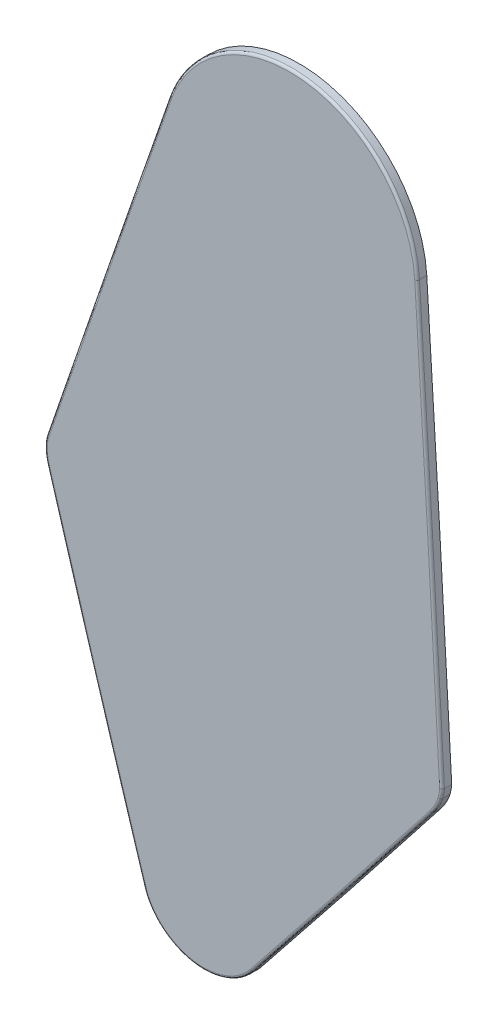
SolidWorks part; units mm, degrees
material "Glass"
ref_plane "Front Plane" through (0, 0, 0) normal (1, 0, 0) x (0, 1, 0)
ref_plane "Top Plane" through (0, 0, 0) normal (0, 0, 1) x (0, 1, 0)
ref_plane "Right Plane" through (0, 0, 0) normal (0, 1, 0) x (-1, 0, 0)
ref_plane "Plane1" through (0, 0, 4) normal (0, 0, 1) x (0, -1, 0)
sketch "Sketch1" plane through (0, 0, 4) normal (0, 0, 1) x (0, -1, 0)
  spline S0 degree 3 poles (-1420.5523, -1258.0609) (-9.2087, -51.8049) (117.8743, 15.8201) (141.0894, -9.406) (141.445, -9.8521) (141.934, -10.5605) (142.0901, -10.8041) (142.3838, -11.2982) (142.5217, -11.5491) (142.9098, -12.3131) (143.134, -12.8375) (143.5137, -13.9162) (143.6701, -14.4742) (143.9078, -15.5951) (143.99, -16.1591) (144.0816, -17.2938) (144.0912, -17.8646) (144.0507, -18.7259) (144.0279, -19.014) (143.9645, -19.5839) (143.8425, -20.4321) (143.6405, -21.2609) (143.386, -22.077) (143.2924, -22.347) (143.0873, -22.8824) (142.9753, -23.1489) (142.3761, -24.4546) (141.7722, -25.418) (140.6814, -26.7427) (140.2836, -27.1652) (139.4464, -27.9421) (139.0049, -28.3001) (138.075, -28.9535) (137.5866, -29.2488) (109.7491, -43.3088) (30.8578, 50.8341) (-150.7129, 1947.6032) knots -3.635484 -3.635484 -3.635484 -3.635484 0.0625 0.0625 0.125 0.125 0.15625 0.15625 0.1875 0.1875 0.25 0.25 0.3125 0.3125 0.375 0.375 0.4375 0.4375 0.46875 0.46875 0.5 0.5625 0.5625 0.59375 0.59375 0.625 0.625 0.75 0.75 0.8125 0.8125 0.875 0.875 0.9375 0.9375 4.253806 4.253806 4.253806 4.253806 only from (139.451, -7.8132) to (135.4716, -30.1628) construction
  spline S1 degree 3 poles (1777.2268, -937.2769) (933.462, 285.5273) (528.1496, 89.7017) (-501.0178, -224.7549) (-1145.5188, -274.5912) (-1876.6031, 131.6295) knots -18.849893 -18.849893 -18.849893 -18.849893 0.5 0.5 27.936686 27.936686 27.936686 27.936686 only from (135.4716, -30.1628) to (69.4721, -50.2962) construction
  spline S2 degree 3 poles (685.4565, -1947.5593) (68.751, 619.5019) (137.0932, -38.6137) (67.761, -50.6717) (67.3235, -50.721) (66.4488, -50.7612) (66.0077, -50.7523) (65.3551, -50.6854) (65.1391, -50.6542) (52.1761, -48.0916) (45.5446, -9.5894) (361.6162, 1927.0025) knots -39.646082 -39.646082 -39.646082 -39.646082 0.25 0.25 0.5 0.5 0.75 0.75 0.875 0.875 8.317936 8.317936 8.317936 8.317936 only from (69.4721, -50.2962) to (64.2894, -50.4457) construction
  spline S3 degree 3 poles (1977.6751, -632.5963) (1342.1316, -413.8375) (672.6843, -261.111) (-511.2007, 148.6626) (-1032.4115, 385.9656) (-1879.9482, -331.711) knots -25.901836 -25.901836 -25.901836 -25.901836 0.5 0.5 22.552972 22.552972 22.552972 22.552972 only from (64.2894, -50.4457) to (-9.0116, -25.0836) construction
  spline S4 degree 3 poles (1150.0007, 1600.8263) (282.016, 191.5059) (54.2647, -60.7375) (-13.8163, -22.8537) (-14.4604, -22.4587) (-15.7169, -21.6116) (-16.3304, -21.1587) (-18.1151, -19.7155) (-19.2052, -18.6644) (-20.6989, -16.9618) (-21.173, -16.373) (-22.0726, -15.1522) (-22.4993, -14.5179) (-23.6944, -12.5609) (-24.368, -11.2054) (-25.2025, -9.0997) (-25.4511, -8.3856) (-25.779, -7.2959) (-25.8808, -6.9296) (-26.069, -6.1906) (-26.1556, -5.817) (-26.5461, -3.9481) (-26.7265, -2.4458) (-26.806, -0.1821) (-26.8005, 0.5742) (-26.7435, 1.7112) (-26.7163, 2.0907) (-26.6455, 2.8505) (-26.6017, 3.2315) (-26.3428, 5.1217) (-26.0087, 6.5969) (-25.3243, 8.7562) (-25.0652, 9.467) (-24.6297, 10.5195) (-24.4767, 10.868) (-24.1547, 11.5604) (-23.9855, 11.9046) (-23.1077, 13.5969) (-22.2976, 14.8736) (-20.9275, 16.6777) (-20.4447, 17.2604) (-19.426, 18.3877) (-18.8873, 18.9349) (-17.2141, 20.4925) (-16.0221, 21.4216) (-14.1245, 22.659) (-13.4736, 23.0453) (-12.1344, 23.7644) (-11.4427, 24.0986) (-9.3448, 25.0015) (-7.9102, 25.4752) (-5.7067, 26.0013) (-4.9635, 26.1457) (41.567, 33.1282) (126.5818, -77.08) (-1831.9128, -772.1245) knots -3.131922 -3.131922 -3.131922 -3.131922 0.0625 0.0625 0.09375 0.09375 0.125 0.125 0.1875 0.1875 0.21875 0.21875 0.25 0.25 0.3125 0.3125 0.34375 0.34375 0.359375 0.359375 0.375 0.375 0.4375 0.4375 0.46875 0.46875 0.484375 0.484375 0.5 0.5 0.5625 0.5625 0.59375 0.59375 0.609375 0.609375 0.625 0.625 0.6875 0.6875 0.71875 0.71875 0.75 0.75 0.8125 0.8125 0.84375 0.84375 0.875 0.875 0.9375 0.9375 0.96875 0.96875 2.871031 2.871031 2.871031 2.871031 only from (-9.0116, -25.0836) to (-1.9329, 26.5003) construction
  spline S5 degree 3 poles (-1735.4311, 802.7914) (-1107.5639, -96.3523) (-534.2598, -4.4267) (727.0682, 69.0855) (1416.0697, 32.8495) (2083.7003, 134.1543) knots -18.972929 -18.972929 -18.972929 -18.972929 0.5 0.5 23.613697 23.613697 23.613697 23.613697 only from (-1.9329, 26.5003) to (86.9211, 31.6717) construction
  spline S6 degree 3 poles (46.5819, -1967.9022) (80.7055, 34.5765) (83.9962, 31.8865) (87.0849, 31.6634) (87.1258, 31.6597) (87.2482, 31.6475) (87.3297, 31.6377) (87.5733, 31.6043) (87.7346, 31.5769) (88.055, 31.5109) (88.2136, 31.4702) (88.4107, 31.4132) (88.4504, 31.4036) (88.5312, 31.3902) (88.5722, 31.3871) (95.3107, 30.7543) (89.3738, -40.8978) (458.6707, 1996.788) knots -4.593389 -4.593389 -4.593389 -4.593389 0.0625 0.0625 0.125 0.125 0.25 0.25 0.5 0.5 0.75 0.75 0.8125 0.8125 0.875 0.875 11.114395 11.114395 11.114395 11.114395 only from (86.9211, 31.6717) to (88.8534, 31.3324) construction
  spline S7 degree 3 poles (342.2934, -1949.7072) (-27.9872, -54.5714) (62.8857, 45.5519) (127.3086, 10.7798) (54.4847, -211.568) (-1409.5405, 1341.1493) knots -23.692811 -23.692811 -23.692811 -23.692811 0.5 0.5 32.440647 32.440647 32.440647 32.440647 only from (88.8534, 31.3324) to (92.2873, 29.4951) construction
  spline S8 degree 3 poles (-1497.707, 1237.4159) (-1108.5525, 731.4491) (-435.8263, 447.6768) (460.4192, -261.7532) (758.3865, -593.0142) (1993.2699, 266.5832) knots -34.605176 -34.605176 -34.605176 -34.605176 0.5 0.5 22.417325 22.417325 22.417325 22.417325 only from (92.2873, 29.4951) to (139.451, -7.8132) construction
  spline S9 degree 3 poles (139.451, -7.8132) (139.9021, -8.1746) (140.3177, -8.5675) (141.0894, -9.406) (141.445, -9.8521) (141.934, -10.5605) (142.0901, -10.8041) (142.3838, -11.2982) (142.5217, -11.5491) (142.9098, -12.3131) (143.134, -12.8375) (143.5137, -13.9162) (143.6701, -14.4742) (143.9078, -15.5951) (143.99, -16.1591) (144.0816, -17.2938) (144.0912, -17.8646) (144.0507, -18.7259) (144.0279, -19.014) (143.9645, -19.5839) (143.8425, -20.4321) (143.6405, -21.2609) (143.386, -22.077) (143.2924, -22.347) (143.0873, -22.8824) (142.9753, -23.1489) (142.3761, -24.4546) (141.7722, -25.418) (140.6814, -26.7427) (140.2836, -27.1652) (139.4464, -27.9421) (139.0049, -28.3001) (138.075, -28.9535) (137.5866, -29.2488) (136.5567, -29.769) (136.0235, -29.9907) (135.4716, -30.1628) knots 0 0 0 0 0.0625 0.0625 0.125 0.125 0.15625 0.15625 0.1875 0.1875 0.25 0.25 0.3125 0.3125 0.375 0.375 0.4375 0.4375 0.46875 0.46875 0.5 0.5625 0.5625 0.59375 0.59375 0.625 0.625 0.75 0.75 0.8125 0.8125 0.875 0.875 0.9375 0.9375 1 1 1 1
  spline S10 degree 3 poles (135.4716, -30.1628) (124.4923, -33.5856) (113.5073, -36.99) (91.5102, -43.7111) (80.4981, -47.027) (69.4721, -50.2962) knots 0 0 0 0 0.5 0.5 1 1 1 1
  spline S11 degree 3 poles (69.4721, -50.2962) (69.0509, -50.421) (68.6245, -50.5215) (67.761, -50.6717) (67.3235, -50.721) (66.4488, -50.7612) (66.0077, -50.7523) (65.3551, -50.6854) (65.1391, -50.6542) (64.7109, -50.5696) (64.4985, -50.5171) (64.2894, -50.4457) knots 0 0 0 0 0.25 0.25 0.5 0.5 0.75 0.75 0.875 0.875 1 1 1 1
  spline S12 degree 3 poles (64.2894, -50.4457) (52.0559, -46.2669) (39.8308, -42.0638) (15.398, -33.607) (3.1907, -29.3525) (-9.0116, -25.0836) knots 0 0 0 0 0.5 0.5 1 1 1 1
  spline S13 degree 3 poles (-9.0116, -25.0836) (-10.4571, -24.5779) (-11.8376, -23.9548) (-13.8163, -22.8537) (-14.4604, -22.4587) (-15.7169, -21.6116) (-16.3304, -21.1587) (-18.1151, -19.7155) (-19.2052, -18.6644) (-20.6989, -16.9618) (-21.173, -16.373) (-22.0726, -15.1522) (-22.4993, -14.5179) (-23.6944, -12.5609) (-24.368, -11.2054) (-25.2025, -9.0997) (-25.4511, -8.3856) (-25.779, -7.2959) (-25.8808, -6.9296) (-26.069, -6.1906) (-26.1556, -5.817) (-26.5461, -3.9481) (-26.7265, -2.4458) (-26.806, -0.1821) (-26.8005, 0.5742) (-26.7435, 1.7112) (-26.7163, 2.0907) (-26.6455, 2.8505) (-26.6017, 3.2315) (-26.3428, 5.1217) (-26.0087, 6.5969) (-25.3243, 8.7562) (-25.0652, 9.467) (-24.6297, 10.5195) (-24.4767, 10.868) (-24.1547, 11.5604) (-23.9855, 11.9046) (-23.1077, 13.5969) (-22.2976, 14.8736) (-20.9275, 16.6777) (-20.4447, 17.2604) (-19.426, 18.3877) (-18.8873, 18.9349) (-17.2141, 20.4925) (-16.0221, 21.4216) (-14.1245, 22.659) (-13.4736, 23.0453) (-12.1344, 23.7644) (-11.4427, 24.0986) (-9.3448, 25.0015) (-7.9102, 25.4752) (-5.7067, 26.0013) (-4.9635, 26.1457) (-3.4595, 26.3714) (-2.6968, 26.4527) (-1.9329, 26.5003) knots 0 0 0 0 0.0625 0.0625 0.09375 0.09375 0.125 0.125 0.1875 0.1875 0.21875 0.21875 0.25 0.25 0.3125 0.3125 0.34375 0.34375 0.359375 0.359375 0.375 0.375 0.4375 0.4375 0.46875 0.46875 0.484375 0.484375 0.5 0.5 0.5625 0.5625 0.59375 0.59375 0.609375 0.609375 0.625 0.625 0.6875 0.6875 0.71875 0.71875 0.75 0.75 0.8125 0.8125 0.84375 0.84375 0.875 0.875 0.9375 0.9375 0.96875 0.96875 1 1 1 1
  spline S14 degree 3 poles (-1.9329, 26.5003) (12.8726, 27.4225) (27.6792, 28.324) (57.2972, 30.0502) (72.1082, 30.8777) (86.9211, 31.6717) knots 0 0 0 0 0.5 0.5 1 1 1 1
  spline S15 degree 3 poles (86.9211, 31.6717) (86.9621, 31.6727) (87.0031, 31.6693) (87.0849, 31.6634) (87.1258, 31.6597) (87.2482, 31.6475) (87.3297, 31.6377) (87.5733, 31.6043) (87.7346, 31.5769) (88.055, 31.5109) (88.2136, 31.4702) (88.4107, 31.4132) (88.4504, 31.4036) (88.5312, 31.3902) (88.5722, 31.3871) (88.6948, 31.3756) (88.7747, 31.3573) (88.8534, 31.3324) knots 0 0 0 0 0.0625 0.0625 0.125 0.125 0.25 0.25 0.5 0.5 0.75 0.75 0.8125 0.8125 0.875 0.875 1 1 1 1
  spline S16 degree 3 poles (88.8534, 31.3324) (89.4765, 31.1359) (90.0773, 30.8753) (91.225, 30.2559) (91.772, 29.8965) (92.2873, 29.4951) knots 0 0 0 0 0.5 0.5 1 1 1 1
  spline S17 degree 3 poles (92.2873, 29.4951) (100.1939, 23.3354) (108.0771, 17.1459) (123.7945, 4.7046) (131.629, -1.5465) (139.451, -7.8132) knots 0 0 0 0 0.5 0.5 1 1 1 1
extrude "Boss-Extrude1" add sketch "Sketch1" against normal blind 2
fillet "Fillet1" radius 0.5 9 edges
